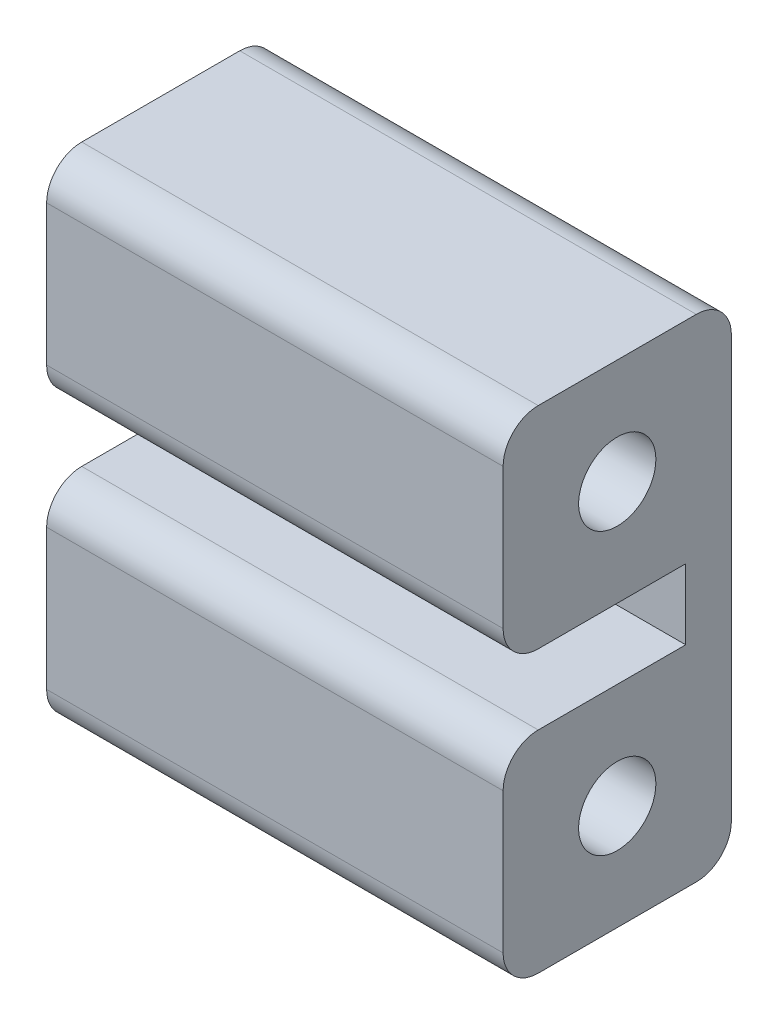
SolidWorks part; units mm, degrees
ref_plane "前视基准面" through (0, 0, 0) normal (0, 0, 1) x (1, 0, 0)
ref_plane "上视基准面" through (0, 0, 0) normal (0, 1, 0) x (1, 0, 0)
ref_plane "右视基准面" through (0, 0, 0) normal (1, 0, 0) x (0, 0, -1)
sketch "草图1" plane through (0, 0, 0) normal (1, 0, 0) x (0, 0, -1)
  line L0 (0, 12.7161) -> (0, 0) construction
  line L1 (-3.25, 7) -> (3.25, 7)
  line L2 (-3.25, 7) -> (-3.25, -7)
  line L3 (-3.25, -7) -> (3.25, -7)
  line L4 (3.25, 7) -> (3.25, -7)
  line L5 (0, 0) -> (30.6148, 0) construction
  line L7 (-3.25, 1) -> (1.95, 1)
  line L8 (-3.25, 1) -> (-3.25, -1)
  line L9 (-3.25, -1) -> (1.95, -1)
  line L10 (1.95, 1) -> (1.95, -1)
  circle A0 centre (0, 4) radius 1.1
  circle A1 centre (0, -4) radius 1.1
  dimension "D5" = 8
  dimension "D6" = 2.2
  dimension "D1" = 6.5
  dimension "D2" = 14
  dimension "D3" = 2
  dimension "D4" = 5.2
extrude "凸台-拉伸1" add sketch "草图1" against normal blind 13 contours L7 L10 L9 L2 L3 L4 L1
fillet "圆角1" radius 1 6 edges at (-6.5, 7, 3.25) (-6.5, 7, -3.25) (-6.5, -7, -3.25) (-6.5, -7, 3.25) (-6.5, 1, 3.25) (-6.5, -1, 3.25)
